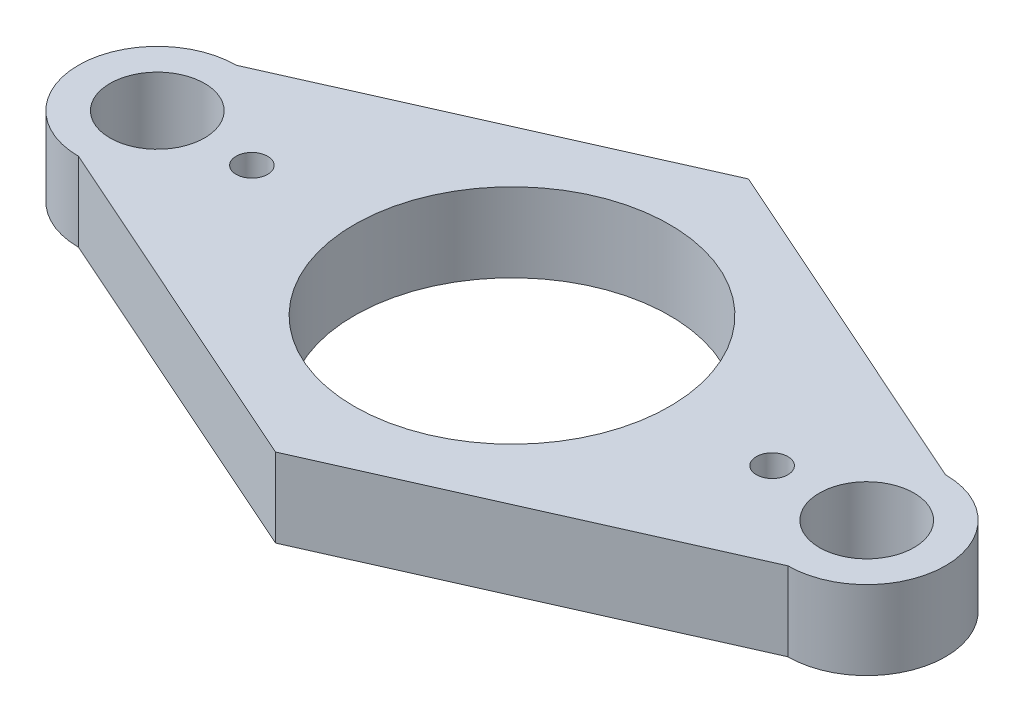
SolidWorks part; units mm, degrees
ref_plane "Спереди" through (0, 0, 0) normal (0, 0, 1) x (1, 0, 0)
ref_plane "Сверху" through (0, 0, 0) normal (0, 1, 0) x (1, 0, 0)
ref_plane "Справа" through (0, 0, 0) normal (1, 0, 0) x (0, 0, -1)
sketch "Эскиз1" plane through (0, 0, 0) normal (0, 1, 0) x (1, 0, 0)
  line L0 (-22.5, -0.8693) -> (0, -0.8693) construction
  line L1 (0, -0.8693) -> (22.5, -0.8693) construction
  line L2 (0, -0.8693) -> (0, 14.1307) construction
  line L3 (0, -0.8693) -> (0, -15.8693) construction
  line L4 (-22.5, -0.8693) -> (-22.5, 4.1307) construction
  line L5 (-22.5, -0.8693) -> (-22.5, -5.8693) construction
  line L6 (22.5, -0.8693) -> (22.5, 4.1307) construction
  line L7 (22.5, -0.8693) -> (22.5, -5.8693) construction
  line L8 (-22.5, 4.1307) -> (0, 14.1307)
  line L9 (0, 14.1307) -> (22.5, 4.1307)
  line L10 (22.5, -5.8693) -> (0, -15.8693)
  line L11 (0, -15.8693) -> (-22.5, -5.8693)
  line L12 (-22.5, -0.8693) -> (-16.5, -0.8693) construction
  line L13 (22.5, -0.8693) -> (16.5, -0.8693) construction
  circle A0 centre (-22.5, -0.8693) radius 3
  circle A1 centre (0, -0.8693) radius 10
  circle A2 centre (22.5, -0.8693) radius 3
  arc A3 (-22.5, 4.1307) -> (-22.5, -5.8693) centre (-22.5, -0.8693) ccw
  arc A4 (22.5, 4.1307) -> (22.5, -5.8693) centre (22.5, -0.8693) cw
  circle A5 centre (-16.5, -0.8693) radius 1
  circle A6 centre (16.5, -0.8693) radius 1
  dimension "D1" = 6
  dimension "D2" = 20
  dimension "D7" = 2
  dimension "D3" = 22.5
  dimension "D4" = 15
  dimension "D5" = 5
  dimension "D6" = 6
extrude "Бобышка-Вытянуть1" add sketch "Эскиз1" along normal blind 5 contours A4 L9 L8 A3 L11 L10 A2 A1 A0
